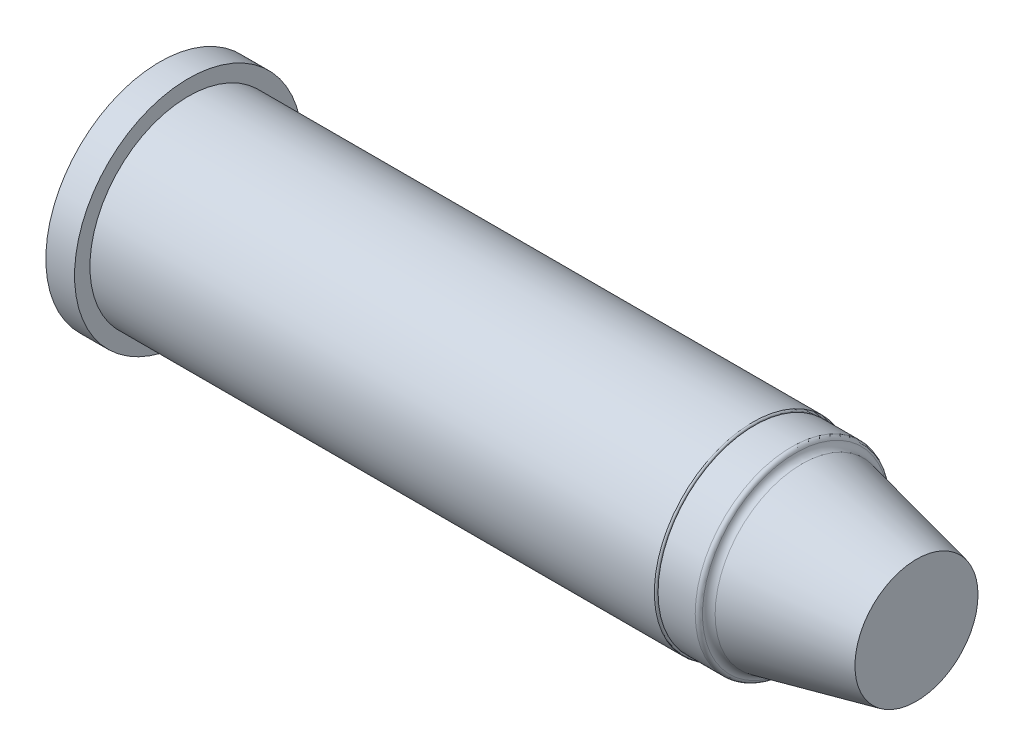
SolidWorks part; units mm, degrees
ref_plane "Plano frontal" through (0, 0, 0) normal (0, 0, 1) x (1, 0, 0)
ref_plane "Plano superior" through (0, 0, 0) normal (0, 1, 0) x (1, 0, 0)
ref_plane "Plano direito" through (0, 0, 0) normal (1, 0, 0) x (0, 0, -1)
sketch "Esboço1" plane through (0, 0, 0) normal (0, 0, 1) x (1, 0, 0)
  line L0 (0, 4.6789) -> (0, 10.2289)
  line L1 (0, 10.2289) -> (1.4, 10.2289)
  line L2 (1.4, 10.2289) -> (1.4, 9.4789)
  line L3 (1.4, 9.4789) -> (28.92, 9.4789)
  line L4 (31, 9.3789) -> (31, 9.3003)
  line L5 (31.3139, 8.9097) -> (36.9, 7.6789)
  line L6 (36.9, 7.6789) -> (36.9, 4.6789)
  line L7 (36.9, 4.6789) -> (0, 4.6789)
  line L8 (31, 9.4789) -> (31, 11.1905) construction
  line L9 (29, 9.3789) -> (29, 9.3989)
  line L10 (29, 9.3789) -> (31, 9.3789)
  line L11 (29, 9.4789) -> (29, 11.1905) construction
  line L13 (1.4, 9.3789) -> (31, 9.3789) construction
  line L14 (1.4, 9.4789) -> (31, 9.4789) construction
  arc A0 (31.3139, 8.9097) -> (31, 9.3003) centre (31.4, 9.3003) cw
  arc A1 (29, 9.3989) -> (28.92, 9.4789) centre (28.92, 9.3989) ccw
  point P18 (31, 8.9789)
  dimension "D8" = 0.4
  dimension "D9" = 0.08
  dimension "D1" = 36.9
  dimension "D2" = 1.4
  dimension "D3" = 5.9
  dimension "D4" = 5.55
  dimension "D5" = 3
  dimension "D6" = 4.3
  dimension "D7" = 4.8
revolve "Revolução1" add sketch "Esboço1" angle 360 about L7
fillet "Filete1" radius 0.2 1 edges at (31, 4.6789, -4.7)
